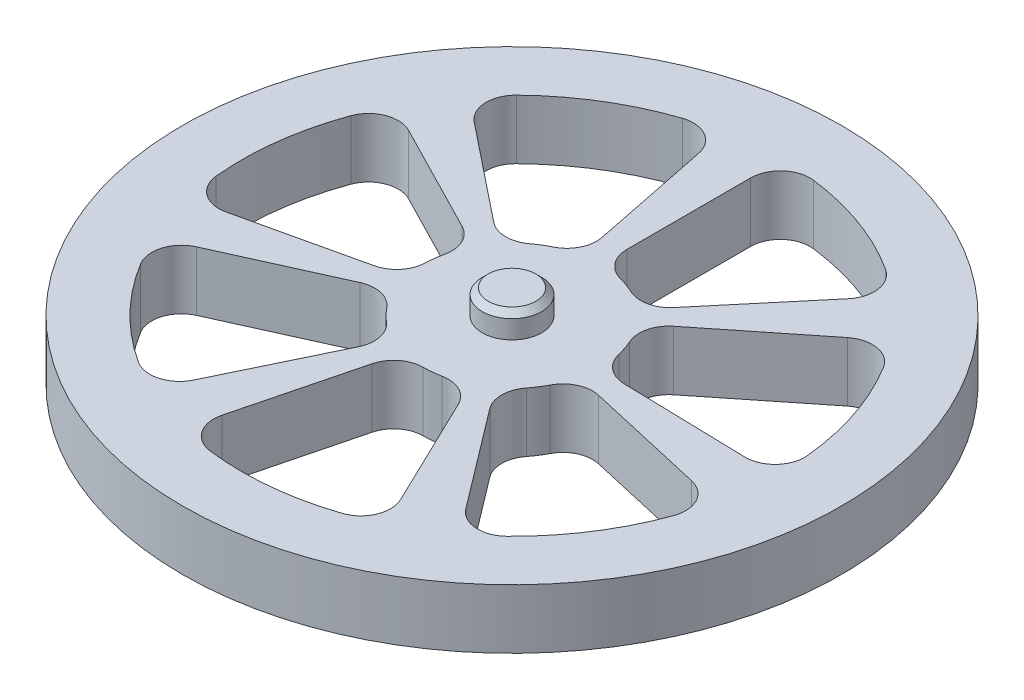
SolidWorks part; units mm, degrees
ref_plane "Front Plane" through (0, 0, 0) normal (0, 0, 1) x (1, 0, 0)
ref_plane "Top Plane" through (0, 0, 0) normal (0, 1, 0) x (1, 0, 0)
ref_plane "Right Plane" through (0, 0, 0) normal (1, 0, 0) x (0, 0, -1)
sketch "Sketch1" plane through (0, 0, 0) normal (0, 1, 0) x (1, 0, 0)
  circle A0 centre (0, 0) radius 55.5
  dimension "D1" = 111
extrude "Boss-Extrude1" add sketch "Sketch1" along normal blind 10
sketch "Sketch2" plane through (0, 10, 0) normal (0, 1, 0) x (1, 0, 0)
  line L0 (0, 15) -> (0, 45.5)
  line L1 (9.6418, 11.4907) -> (29.2468, 34.855)
  arc A0 (9.6418, 11.4907) -> (0, 15) centre (0, 0) ccw
  arc A1 (29.2468, 34.855) -> (0, 45.5) centre (0, 0) ccw
  circle A2 centre (0, 0) radius 55.5 construction
  dimension "D1" = 15
  dimension "D2" = 10
  dimension "D3" = 40
extrude "Cut-Extrude1" cut sketch "Sketch2" against normal through all
fillet "Fillet1" radius 5 4 edges at (29.2468, 5, -34.855) (0, 5, -45.5) (9.6418, 5, -11.4907) (0, 5, -15)
pattern_circular "CirPattern1" count 7 over 360 about axis through (0, 0, 0) along (0, 1, 0) of "Cut-Extrude1", "Fillet1"
sketch "Sketch3" plane through (0, 10, 0) normal (0, 1, 0) x (1, 0, 0)
  circle A0 centre (0, 0) radius 5
  dimension "D1" = 10
extrude "Boss-Extrude2" add sketch "Sketch3" along normal blind 4.1
chamfer "Chamfer1" distance 1 angle 45 1 edges at (0, 14.1, 5)
